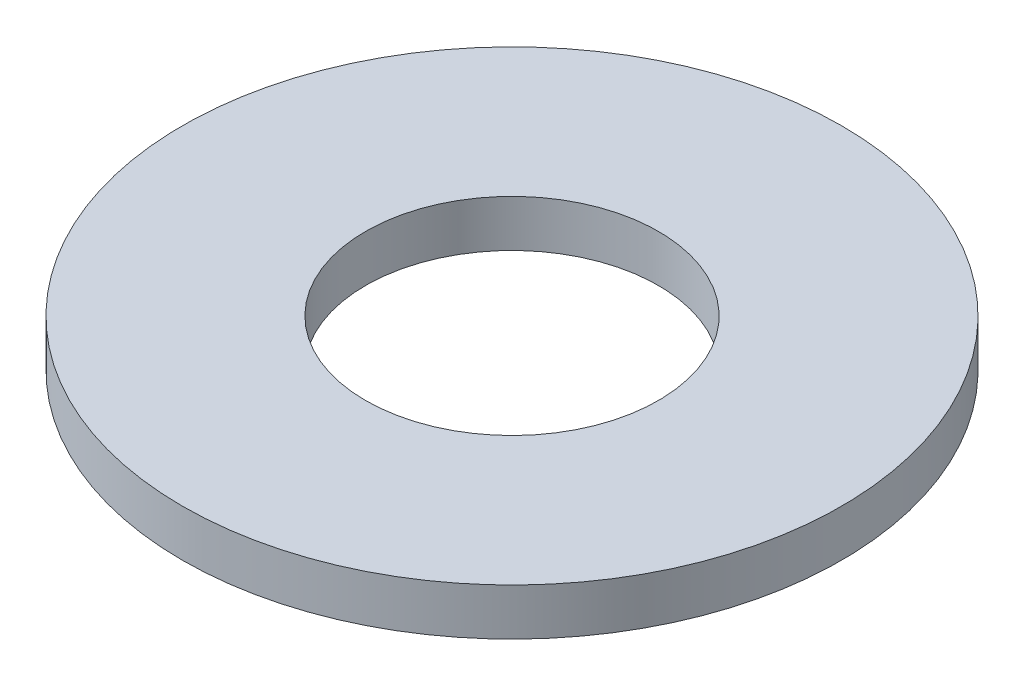
SolidWorks part; units mm, degrees
ref_plane "Front Plane" through (0, 0, 0) normal (0, 0, 1) x (1, 0, 0)
ref_plane "Top Plane" through (0, 0, 0) normal (0, 1, 0) x (1, 0, 0)
ref_plane "Right Plane" through (0, 0, 0) normal (1, 0, 0) x (0, 0, -1)
sketch "Sketch1" plane through (0, 0, 0) normal (0, 1, 0) x (1, 0, 0)
  circle A0 centre (0, 0) radius 7.1438
  circle A1 centre (0, 0) radius 3.175
  dimension "D1" = 6.35
  dimension "D2" = 14.2875
extrude "Boss-Extrude1" add sketch "Sketch1" along normal blind 1.016
